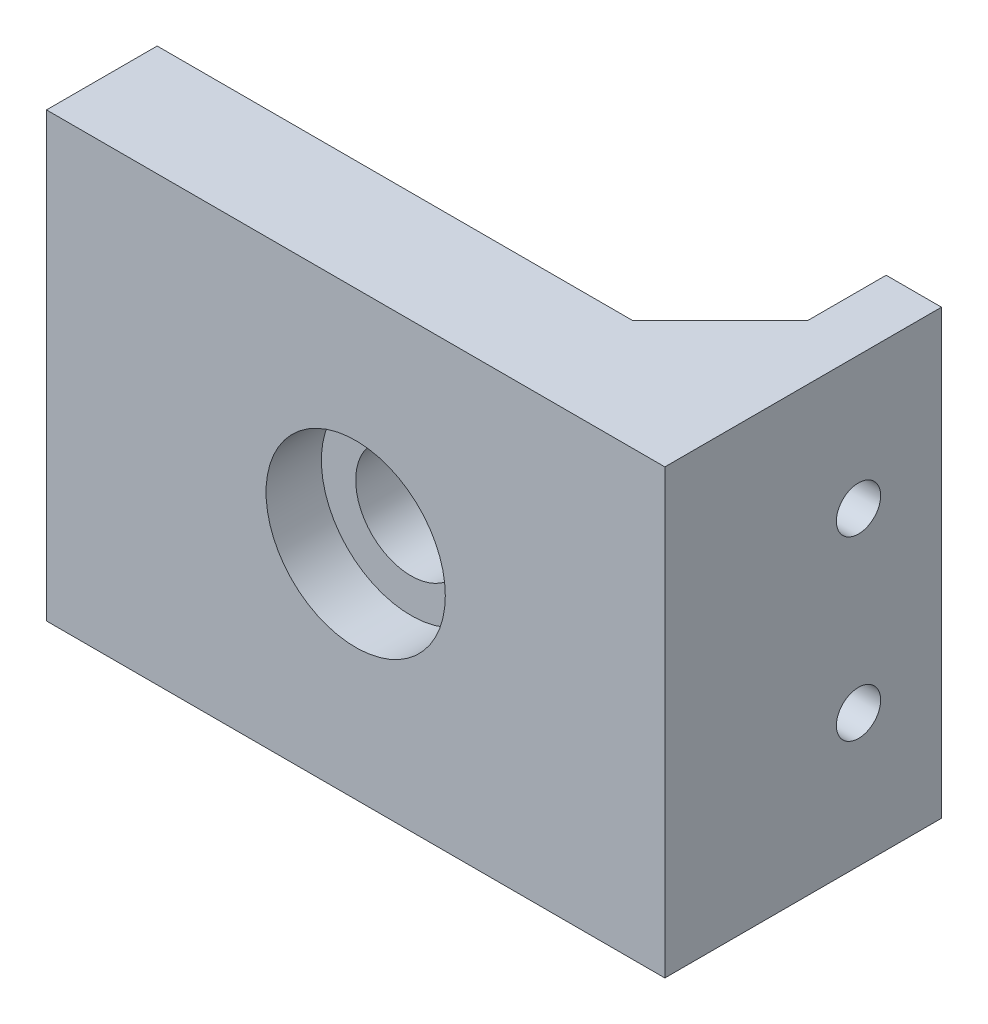
SolidWorks part; units mm, degrees
ref_plane "Front Plane" through (0, 0, 0) normal (0, 0, 1) x (1, 0, 0)
ref_plane "Top Plane" through (0, 0, 0) normal (0, 1, 0) x (1, 0, 0)
ref_plane "Right Plane" through (0, 0, 0) normal (1, 0, 0) x (0, 0, -1)
sketch "Sketch1" plane through (0, 0, 0) normal (0, 0, 1) x (1, 0, 0)
  line L1 (-27.94, 20) -> (27.94, 20)
  line L2 (-27.94, 20) -> (-27.94, -20)
  line L3 (-27.94, -20) -> (27.94, -20)
  line L4 (27.94, 20) -> (27.94, -20)
  line L5 (-27.94, 20) -> (27.94, -20) construction
  line L6 (-27.94, -20) -> (27.94, 20) construction
  circle A0 centre (0, 0) radius 5
  point P0 (0, 0)
  dimension "D3" = 10
  dimension "D1" = 55.88
  dimension "D2" = 40
extrude "Boss-Extrude1" add sketch "Sketch1" along normal blind 10
sketch "Sketch2" plane through (0, 0, 10) normal (0, 0, 1) x (1, 0, 0)
  circle A0 centre (0, 0) radius 8.1
  dimension "D1" = 16.2
extrude "Cut-Extrude1" cut sketch "Sketch2" against normal blind 5
sketch "Sketch3" plane through (0, 0, 0) normal (0, 0, -1) x (-1, 0, 0)
  line L0 (27.94, -20) -> (-27.94, -20) construction
  line L1 (-27.94, 20) -> (-22.94, 20)
  line L2 (-27.94, 20) -> (-27.94, -20)
  line L3 (-27.94, -20) -> (-22.94, -20)
  line L4 (-22.94, 20) -> (-22.94, -20)
  dimension "D1" = 5
extrude "Boss-Extrude3" add sketch "Sketch3" along normal blind 15
sketch "Sketch4" plane through (0, 20, 0) normal (0, 1, 0) x (1, 0, 0)
  line L0 (15.0054, 0) -> (22.94, 7.9346)
  line L1 (22.94, 0) -> (-27.94, 0) construction
  line L2 (22.94, 15) -> (22.94, 0) construction
  dimension "D1" = 45
rib "Rib1" sketch "Sketch4" sketch "Sketch4" thickness 5 extrusion direction parallel to sketch draft on no parameters "D1"=5
mirror "Mirror1" about plane through (0, 0, 0) normal (0, 1, 0) of "Rib1"
sketch "Sketch5" plane through (22.94, 0, 0) normal (-1, 0, 0) x (0, 0, 1)
  line L0 (-15, 20) -> (0, -20) construction
  line L1 (0, 20) -> (0, -20) construction
  line L2 (10, -20) -> (0, -20) construction
  line L3 (-7.5, 0) -> (-7.5, 8) construction
  line L4 (-7.5, 0) -> (-12.5103, 0) construction
  circle A0 centre (-7.5, 8) radius 2
  circle A1 centre (-7.5, -8) radius 2
  dimension "D1" = 8
extrude "Cut-Extrude2" cut sketch "Sketch5" against normal blind 15
